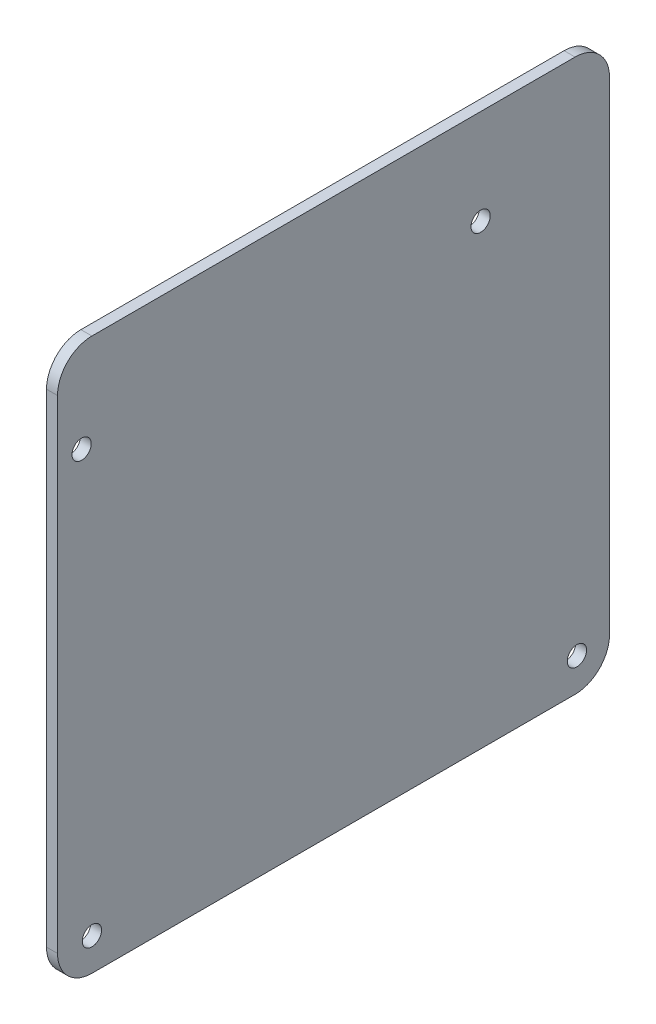
SolidWorks part; units mm, degrees
ref_plane "Front Plane" through (0, 0, 0) normal (0, 0, 1) x (1, 0, 0)
ref_plane "Top Plane" through (0, 0, 0) normal (0, 1, 0) x (1, 0, 0)
ref_plane "Right Plane" through (0, 0, 0) normal (1, 0, 0) x (0, 0, -1)
sketch "Sketch1" plane through (0, 0, 0) normal (1, 0, 0) x (0, 0, -1)
  line L1 (-35.115, -40.115) -> (35.115, -40.115)
  line L2 (-40.115, -35.115) -> (-40.115, 35.115)
  line L3 (-35.115, 40.115) -> (35.115, 40.115)
  line L4 (40.115, -35.115) -> (40.115, 35.115)
  line L5 (-40.115, -40.115) -> (40.115, 40.115) construction
  line L6 (-40.115, 40.115) -> (40.115, -40.115) construction
  circle A0 centre (-36.615, 26.615) radius 1.4
  circle A1 centre (21.3842, 26.315) radius 1.4
  circle A2 centre (35.3842, -35.385) radius 1.4
  circle A3 centre (-35.115, -35.385) radius 1.4
  arc A4 (-40.115, -35.115) -> (-35.115, -40.115) centre (-35.115, -35.115) ccw
  arc A5 (35.115, -40.115) -> (40.115, -35.115) centre (35.115, -35.115) ccw
  arc A6 (40.115, 35.115) -> (35.115, 40.115) centre (35.115, 35.115) ccw
  arc A7 (-35.115, 40.115) -> (-40.115, 35.115) centre (-35.115, 35.115) ccw
  point P0 (0, 0)
  point P26 (21.385, 26.615)
  point P27 (21.3539, 24.7166)
  dimension "D2" = 2.8
  dimension "D5" = 58
  dimension "D6" = 14
  dimension "D8" = 1.5
  dimension "D9" = 5
  dimension "D1" = 80.23
  dimension "D3" = 13.5
  dimension "D4" = 3.5
  dimension "D7" = 61.7
  dimension "D10" = 62
  dimension "D11" = 0.3
extrude "Boss-Extrude1" add sketch "Sketch1" along normal mid plane 1.6
